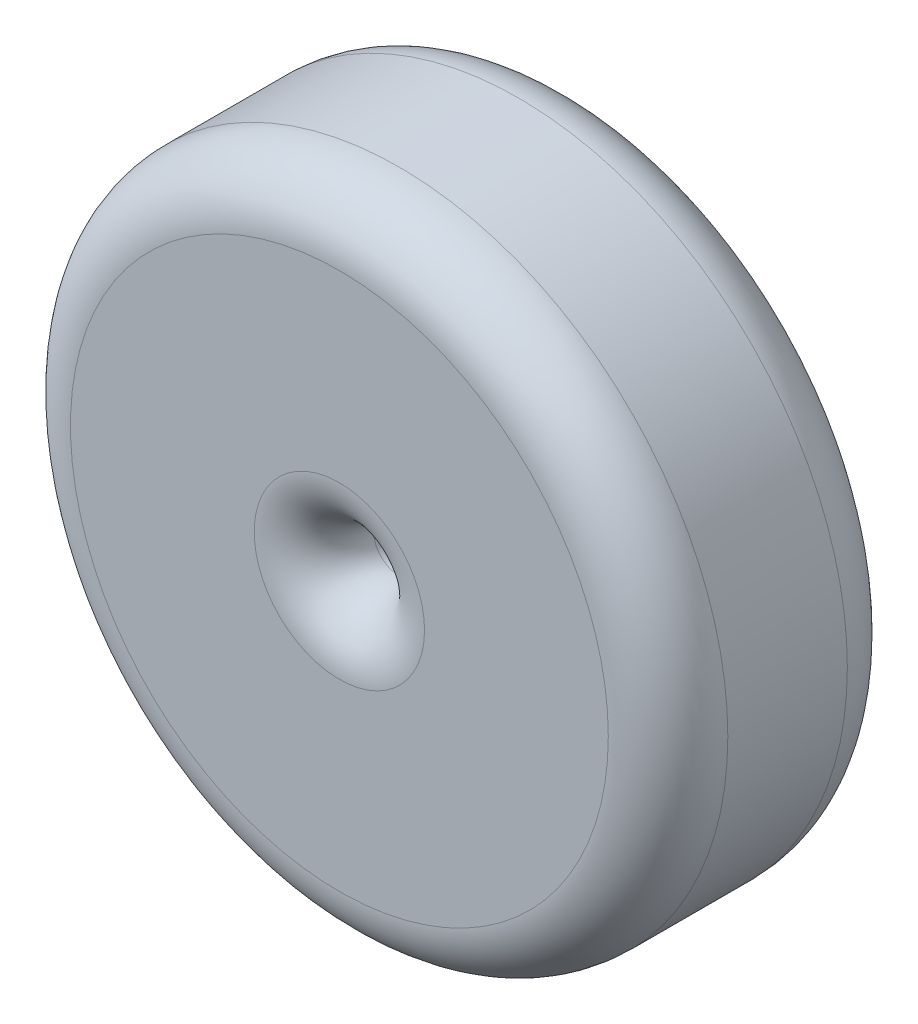
SolidWorks part; units mm, degrees
ref_plane "前视基准面" through (0, 0, 0) normal (0, 0, 1) x (1, 0, 0)
ref_plane "上视基准面" through (0, 0, 0) normal (0, 1, 0) x (1, 0, 0)
ref_plane "右视基准面" through (0, 0, 0) normal (1, 0, 0) x (0, 0, -1)
other "Configuration Table"
sketch "草图1" plane through (0, 0, 0) normal (0, 0, 1) x (1, 0, 0)
  circle A0 centre (0, 0) radius 22
  circle A1 centre (0, 0) radius 1.7
extrude "凸台-拉伸1" add sketch "草图1" along normal mid plane 16
fillet "圆角1" radius 4 4 edges at (1.7, 0, -8) (1.7, 0, 8) (22, 0, -8) (22, 0, 8)
